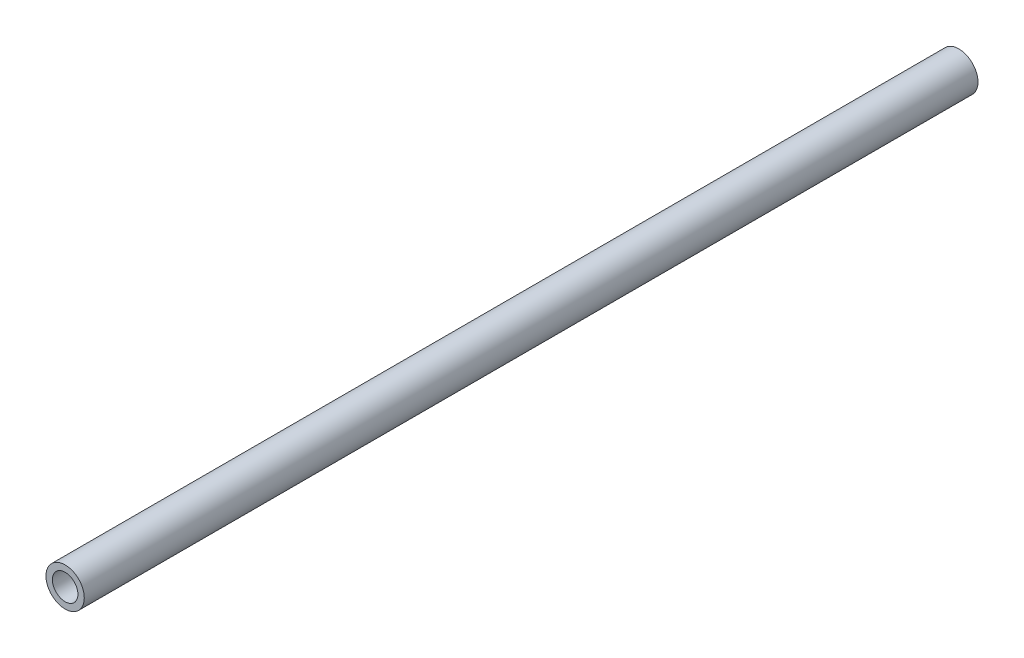
SolidWorks part; units mm, degrees
ref_plane "Спереди" through (0, 0, 0) normal (0, 0, 1) x (1, 0, 0)
ref_plane "Сверху" through (0, 0, 0) normal (0, 1, 0) x (1, 0, 0)
ref_plane "Справа" through (0, 0, 0) normal (1, 0, 0) x (0, 0, -1)
sketch "Эскиз1_fr" plane through (0, 0, 0) normal (0, 0, 1) x (1, 0, 0)
  circle A0 centre (0, 0) radius 10
  circle A1 centre (0, 0) radius 15
  dimension "D1" = 5
extrude "Бобышка-Вытянуть1" add sketch "Эскиз1_fr" along normal blind 700
